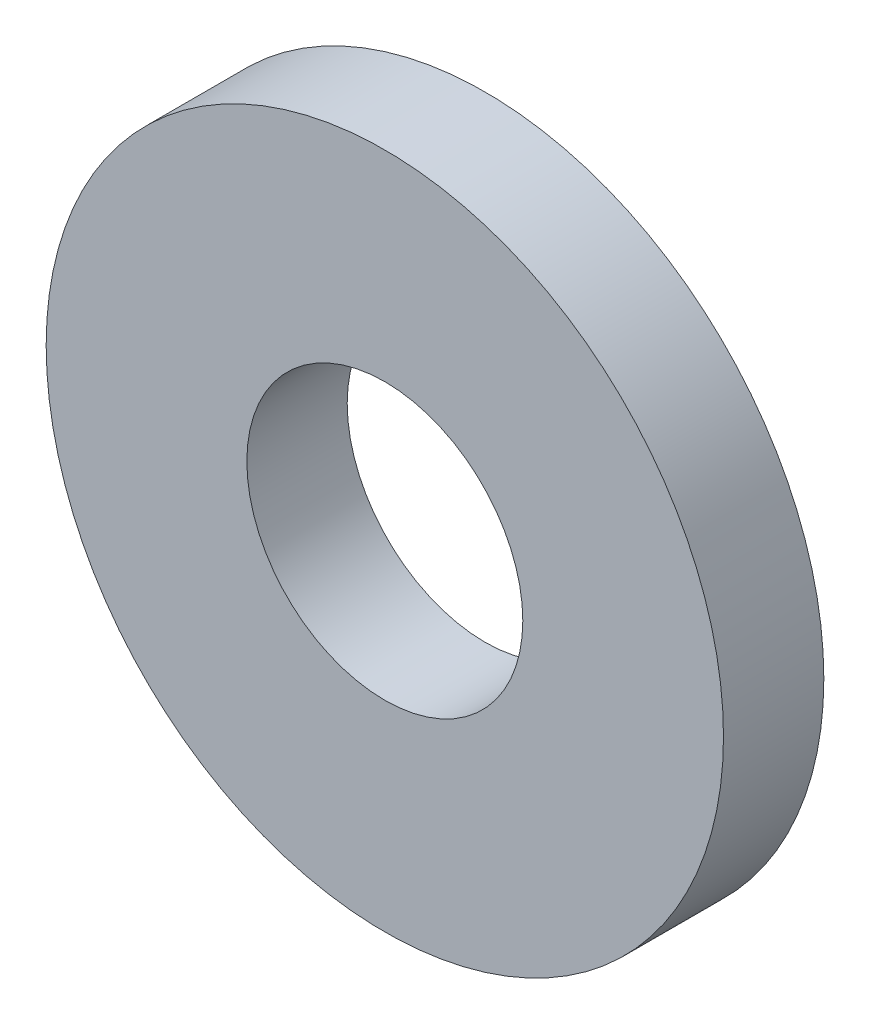
SolidWorks part; units mm, degrees
material "Bronze pour coussinet"
ref_plane "Plan de face" through (0, 0, 0) normal (0, 0, 1) x (1, 0, 0)
ref_plane "Plan de dessus" through (0, 0, 0) normal (0, 1, 0) x (1, 0, 0)
ref_plane "Plan de droite" through (0, 0, 0) normal (1, 0, 0) x (0, 0, -1)
sketch "Esquisse1" plane through (0, 0, 0) normal (0, 0, 1) x (1, 0, 0)
  circle A0 centre (0, 0) radius 13.5
  circle A1 centre (0, 0) radius 5.5
  dimension "D1" = 27
  dimension "D2" = 11
extrude "Extrusion1" add sketch "Esquisse1" along normal blind 4
